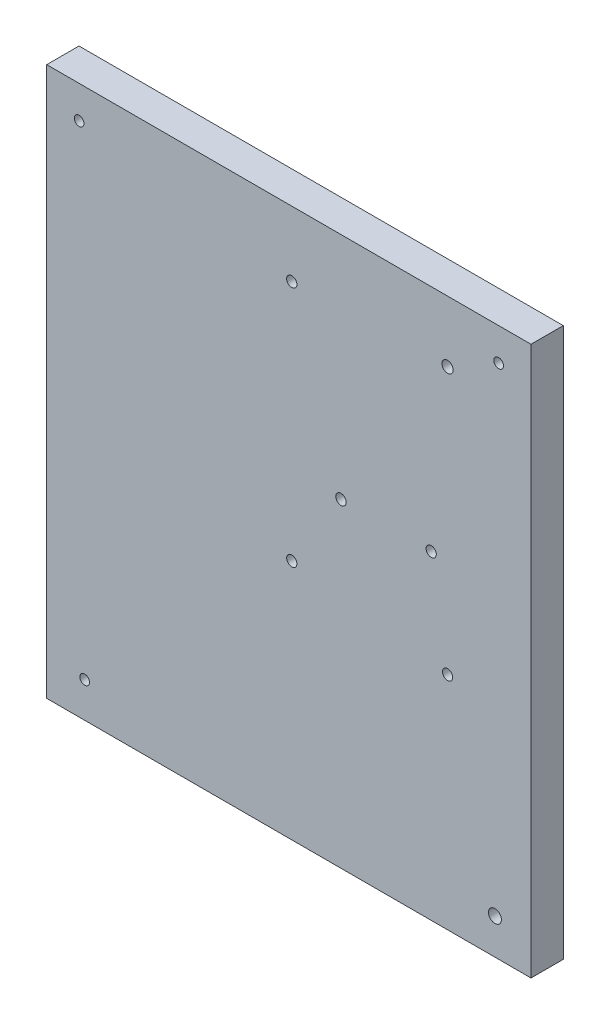
SolidWorks part; units mm, degrees
ref_plane "Plano frontal" through (0, 0, 0) normal (0, 0, 1) x (1, 0, 0)
ref_plane "Plano superior" through (0, 0, 0) normal (0, 1, 0) x (1, 0, 0)
ref_plane "Plano direito" through (0, 0, 0) normal (1, 0, 0) x (0, 0, -1)
sketch "Esboço1" plane through (0, 0, 0) normal (0, 0, 1) x (1, 0, 0)
  line L1 (0, 0) -> (150, 0)
  line L2 (0, 0) -> (0, 170)
  line L3 (0, 170) -> (150, 170)
  line L4 (150, 0) -> (150, 170)
  dimension "D1" = 150
  dimension "D2" = 170
extrude "Ressalto-extrusão1" add sketch "Esboço1" along normal blind 10
sketch "Esboço2" plane through (0, 0, 0) normal (0, 0, 1) x (1, 0, 0)
  circle A0 centre (10.033, 159.9402) radius 1.5
  circle A1 centre (139.9789, 159.9402) radius 1.5
  circle A2 centre (138.8301, 11.0363) radius 1.9976
  circle A3 centre (11.7557, 10.9268) radius 1.5
  circle A4 centre (75.9024, 149.76) radius 1.5875
  circle A5 centre (124.1624, 151.03) radius 1.7383
  circle A6 centre (119.0824, 98.96) radius 1.5875
  circle A7 centre (91.1424, 98.96) radius 1.6201
  circle A8 centre (124.1624, 68.48) radius 1.5875
  circle A9 centre (75.9024, 74.83) radius 1.5875
  dimension "D3" = 3
  dimension "D6" = 3
  dimension "D9" = 3.9952
  dimension "D12" = 3
  dimension "D1" = 0
  dimension "D2" = 0
  dimension "D4" = 0
  dimension "D5" = 0
  dimension "D7" = 0
  dimension "D8" = 0
  dimension "D10" = 0
  dimension "D11" = 0
extrude "Corte-extrusão1" cut sketch "Esboço2" along normal blind 46
